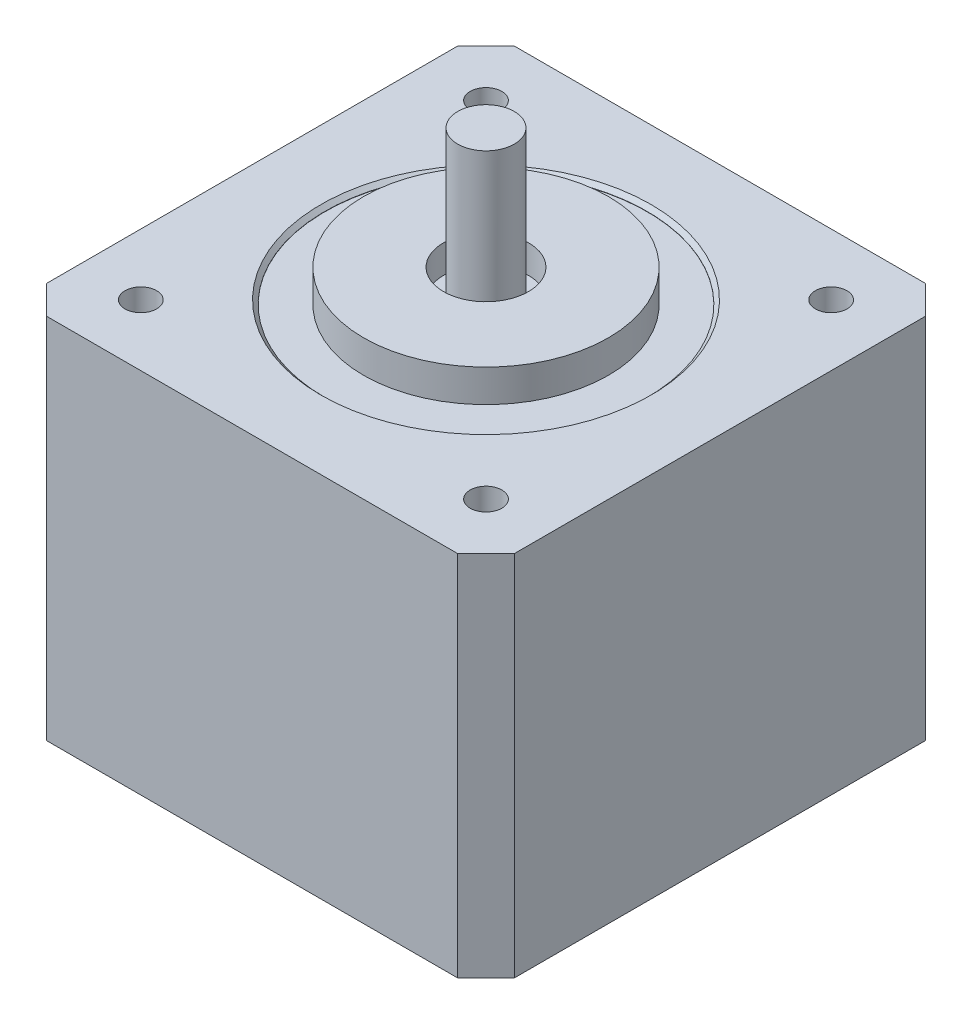
SolidWorks part; units mm, degrees
ref_plane "Front Plane" through (0, 0, 0) normal (0, 0, 1) x (1, 0, 0)
ref_plane "Top Plane" through (0, 0, 0) normal (0, 1, 0) x (1, 0, 0)
ref_plane "Right Plane" through (0, 0, 0) normal (1, 0, 0) x (0, 0, -1)
sketch "Sketch1" plane through (0, 0, 0) normal (0, 1, 0) x (1, 0, 0)
  line L1 (-21.0185, -21.0185) -> (21.0185, -21.0185)
  line L2 (-21.0185, -21.0185) -> (-21.0185, 21.0185)
  line L3 (-21.0185, 21.0185) -> (21.0185, 21.0185)
  line L4 (21.0185, -21.0185) -> (21.0185, 21.0185)
  line L5 (-21.0185, -21.0185) -> (21.0185, 21.0185) construction
  line L6 (-21.0185, 21.0185) -> (21.0185, -21.0185) construction
  point P0 (0, 0)
extrude "Boss-Extrude1" add sketch "Sketch1" along normal blind 33.02
chamfer "Chamfer1" distance 2.54 angle 45 4 edges at (-21.0185, 16.51, -21.0185) (-21.0185, 16.51, 21.0185) (21.0185, 16.51, -21.0185) (21.0185, 16.51, 21.0185)
sketch "Sketch2" plane through (0, 33.02, 0) normal (0, 1, 0) x (1, 0, 0)
  circle A0 centre (0, 0) radius 10.9982
  circle A1 centre (0, 0) radius 3.81
extrude "Boss-Extrude2" add sketch "Sketch2" along normal blind 2.54
sketch "Sketch3" plane through (0, 33.02, 0) normal (0, 1, 0) x (1, 0, 0)
  circle A0 centre (0, 0) radius 14.478
  circle A1 centre (0, 0) radius 10.9982
extrude "Cut-Extrude1" cut sketch "Sketch3" against normal blind 0.381
chamfer "Chamfer2" distance 0.3556 angle 45 1 edges at (0, 33.02, 14.478)
sketch "Sketch4" plane through (0, 33.02, 0) normal (0, 1, 0) x (1, 0, 0)
  circle A0 centre (0, 0) radius 2.54
extrude "Boss-Extrude3" add sketch "Sketch4" along normal blind 13.3858
sketch "Sketch5" plane through (0, 33.02, 0) normal (0, 1, 0) x (1, 0, 0)
  line L0 (18.4785, 21.0185) -> (-18.4785, 21.0185) construction
  line L1 (-21.0185, 18.4785) -> (-21.0185, -18.4785) construction
  line L2 (0, 0) -> (-15.5067, 15.5067) construction
  line L3 (0, 0) -> (15.5067, 15.5067) construction
  line L4 (0, 0) -> (15.5067, -15.5067) construction
  line L5 (0, 0) -> (-15.5067, -15.5067) construction
  circle A0 centre (-15.5067, 15.5067) radius 1.4224
  circle A1 centre (15.5067, 15.5067) radius 1.4224
  circle A2 centre (-15.5067, -15.5067) radius 1.4224
  circle A3 centre (15.5067, -15.5067) radius 1.4224
  dimension "D3" = 2.8448
  dimension "D1" = 5.5118
  dimension "D2" = 5.5118
extrude "Cut-Extrude2" cut sketch "Sketch5" against normal through all
